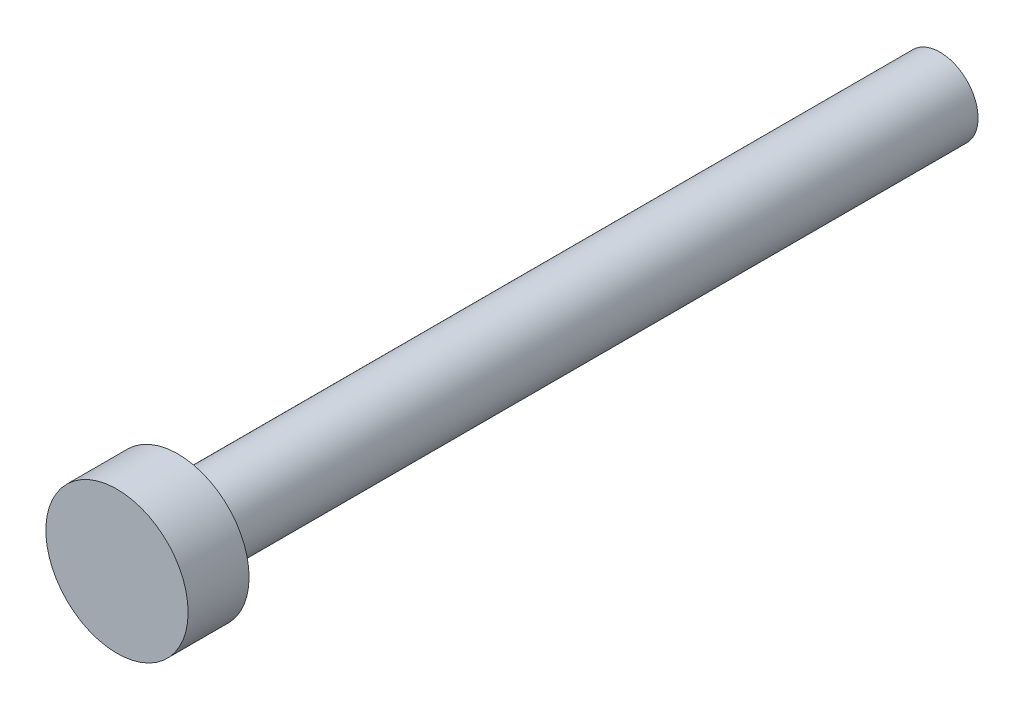
SolidWorks part; units mm, degrees
ref_plane "Plan de face" through (0, 0, 0) normal (0, 0, 1) x (1, 0, 0)
ref_plane "Plan de dessus" through (0, 0, 0) normal (0, 1, 0) x (1, 0, 0)
ref_plane "Plan de droite" through (0, 0, 0) normal (1, 0, 0) x (0, 0, -1)
sketch "Esquisse1" plane through (0, 0, 0) normal (0, 0, 1) x (1, 0, 0)
  circle A0 centre (0, 0) radius 2.8
  dimension "D1" = 5.6
extrude "Boss.-Extru.1" add sketch "Esquisse1" along normal blind 2.4
sketch "Esquisse2" plane through (0, 0, 0) normal (0, 0, -1) x (-1, 0, 0)
  circle A0 centre (0, 0) radius 1.5
  dimension "D1" = 3
extrude "Boss.-Extru.2" add sketch "Esquisse2" along normal blind 30
